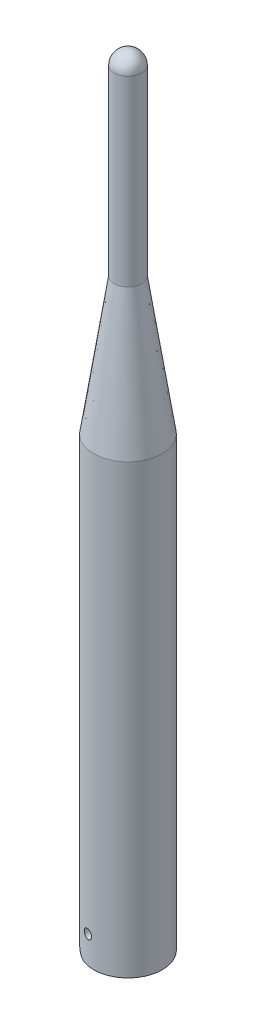
SolidWorks part; units mm, degrees
ref_plane "Front Plane" through (0, 0, 0) normal (0, 0, 1) x (1, 0, 0)
ref_plane "Top Plane" through (0, 0, 0) normal (0, 1, 0) x (1, 0, 0)
ref_plane "Right Plane" through (0, 0, 0) normal (1, 0, 0) x (0, 0, -1)
sketch "Sketch2" plane through (0, 0, 0) normal (0, 0, 1) x (1, 0, 0)
  line L0 (0, 0) -> (0, 78) construction
  line L1 (7.5, -72) -> (7.5, 8)
  line L2 (7.5, 8) -> (3, 38)
  line L3 (3, 38) -> (3, 78)
  line L4 (0, 81) -> (0, -72)
  line L5 (0, -72) -> (7.5, -72)
  arc A0 (3, 78) -> (0, 81) centre (0, 78) ccw
  point P5 (0, 39)
  dimension "D1" = 80
  dimension "D3" = 7.5
  dimension "D4" = 40
  dimension "D5" = 3
revolve "Revolve1" add sketch "Sketch2" angle 360 about L4
sketch "Sketch3" plane through (0, -72, 0) normal (0, -1, 0) x (1, 0, 0)
  circle A1 centre (0, 0) radius 7.5
  circle A2 centre (0, 0) radius 7.5
  dimension "D1" = 0
extrude "Boss-Extrude1" add sketch "Sketch3" along normal blind 18
sketch "Sketch4" plane through (0, -90, 0) normal (0, -1, 0) x (1, 0, 0)
  line L0 (0, 0) -> (-7.5, 0) construction
  line L1 (-6.3443, 4) -> (5.5, 4)
  line L2 (5.5, 4) -> (5.5, -0.5854)
  line L3 (5.5, -4) -> (5.5, 0.5854)
  line L4 (-6.3443, -4) -> (5.5, -4)
  circle A0 centre (0, 0) radius 7.5 construction
  arc A1 (-6.3443, 4) -> (-6.3443, -4) centre (0, 0) ccw
  dimension "D1" = 8
  dimension "D2" = 5.5
extrude "Cut-Extrude1" cut sketch "Sketch4" against normal blind 12
chamfer "Chamfer1" distance 2 angle 45 1 edges at (-7.5, -78, 0)
sketch "Sketch6" plane through (0, 0, -4) normal (0, 0, 1) x (1, 0, 0)
  line L0 (-6.3443, -76) -> (-6.3443, -90) construction
  line L1 (-6.3443, -86) -> (-6.3443, -90)
  line L2 (-6.3443, -90) -> (5.5, -90) construction
  line L3 (-6.3443, -90) -> (-2.3443, -90)
  arc A0 (-2.3443, -90) -> (-6.3443, -86) centre (-2.3443, -86) cw
  dimension "D2" = 4
extrude "Cut-Extrude2" cut sketch "Sketch6" against normal through all and the other way through all
sketch "Sketch7" plane through (0, 0, -4) normal (0, 0, 1) x (1, 0, 0)
  line L0 (-2.3443, -90) -> (7.5, -90) construction
  line L1 (-7.5, 8) -> (-7.5, -76) construction
  circle A0 centre (-1.5, -84) radius 1
  dimension "D3" = 2
  dimension "D1" = 6
  dimension "D2" = 6
extrude "Cut-Extrude3" cut sketch "Sketch7" against normal through all and the other way through all
